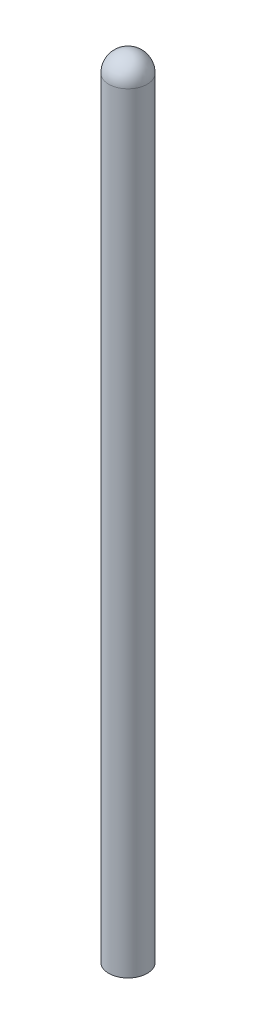
SolidWorks part; units mm, degrees
ref_plane "前视基准面" through (0, 0, 0) normal (0, 0, 1) x (1, 0, 0)
ref_plane "上视基准面" through (0, 0, 0) normal (0, 1, 0) x (1, 0, 0)
ref_plane "右视基准面" through (0, 0, 0) normal (1, 0, 0) x (0, 0, -1)
other "Configuration Table"
sketch "草图1" plane through (0, 0, 0) normal (0, 1, 0) x (1, 0, 0)
  circle A0 centre (0, 0) radius 0.75
  dimension "D1" = 1.5
extrude "凸台-拉伸1" add sketch "草图1" along normal blind 30
sketch "草图2" plane through (0, 0, 0) normal (1, 0, 0) x (0, 0, -1)
  line L0 (0.75, 30) -> (-0.75, 30) construction
  line L1 (0, 30.75) -> (0, 29.25)
  arc A0 (0, 29.25) -> (0, 30.75) centre (0, 30) ccw
revolve "旋转1" add sketch "草图2" angle 360 about L1
